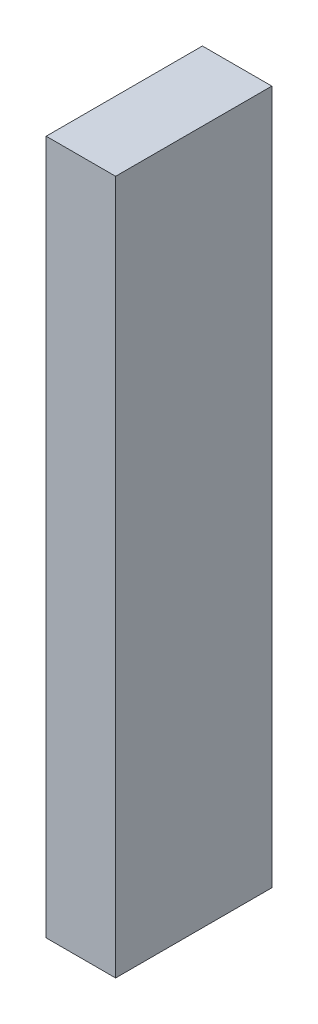
SolidWorks part; units mm, degrees
material "Teak"
ref_plane "Front Plane" through (0, 0, 0) normal (0, 0, 1) x (1, 0, 0)
ref_plane "Top Plane" through (0, 0, 0) normal (0, 1, 0) x (1, 0, 0)
ref_plane "Right Plane" through (0, 0, 0) normal (1, 0, 0) x (0, 0, -1)
sketch "Sketch1" plane through (0, 0, 0) normal (0, 1, 0) x (1, 0, 0)
  line L0 (0, 0) -> (-20, 0)
  line L1 (-20, 0) -> (-20, 45)
  line L2 (-20, 45) -> (0, 45)
  line L3 (0, 45) -> (0, 0)
  dimension "D1" = 20
  dimension "D2" = 45
extrude "Boss-Extrude1" add sketch "Sketch1" along normal blind 200
